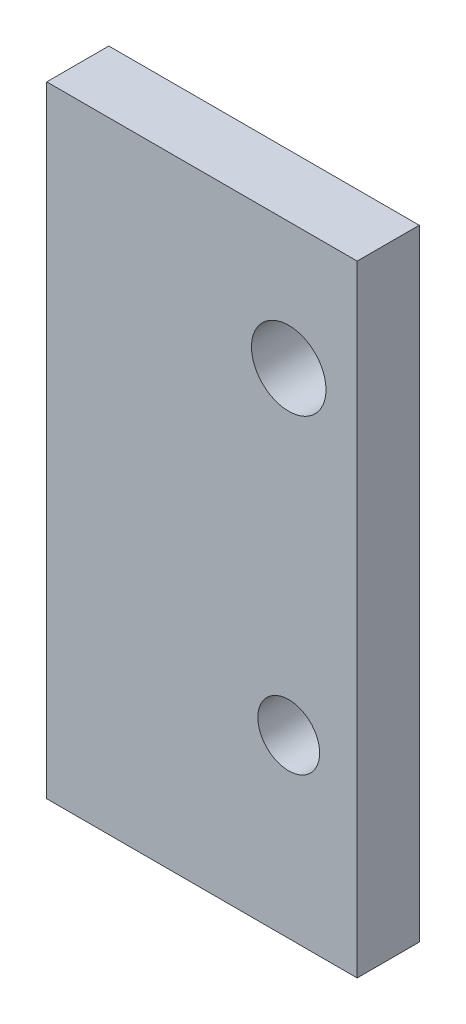
SolidWorks part; units mm, degrees
ref_plane "Front Plane" through (0, 0, 0) normal (0, 0, 1) x (1, 0, 0)
ref_plane "Top Plane" through (0, 0, 0) normal (0, 1, 0) x (1, 0, 0)
ref_plane "Right Plane" through (0, 0, 0) normal (1, 0, 0) x (0, 0, -1)
sketch "Sketch1" plane through (0, 0, 0) normal (0, 0, 1) x (1, 0, 0)
  line L1 (-6.35, 12.7) -> (6.35, 12.7)
  line L2 (-6.35, 12.7) -> (-6.35, -12.7)
  line L3 (-6.35, -12.7) -> (6.35, -12.7)
  line L4 (6.35, 12.7) -> (6.35, -12.7)
  line L5 (-6.35, 12.7) -> (6.35, -12.7) construction
  line L6 (-6.35, -12.7) -> (6.35, 12.7) construction
  point P0 (0, 0)
  dimension "D1" = 12.7
  dimension "D2" = 25.4
extrude "Boss-Extrude1" add sketch "Sketch1" along normal blind 2.54
sketch "Sketch2" plane through (0, 0, 2.54) normal (0, 0, 1) x (1, 0, 0)
  line L0 (6.35, -12.7) -> (6.35, 12.7) construction
  circle A0 centre (3.55, 7.5019) radius 1.524
  circle A1 centre (3.55, -5.4981) radius 1.2637
  dimension "D1" = 3.048
  dimension "D2" = 2.5273
  dimension "D3" = 2.8
  dimension "D4" = 2.8
  dimension "D5" = 13
extrude "Cut-Extrude1" cut sketch "Sketch2" against normal up to next
